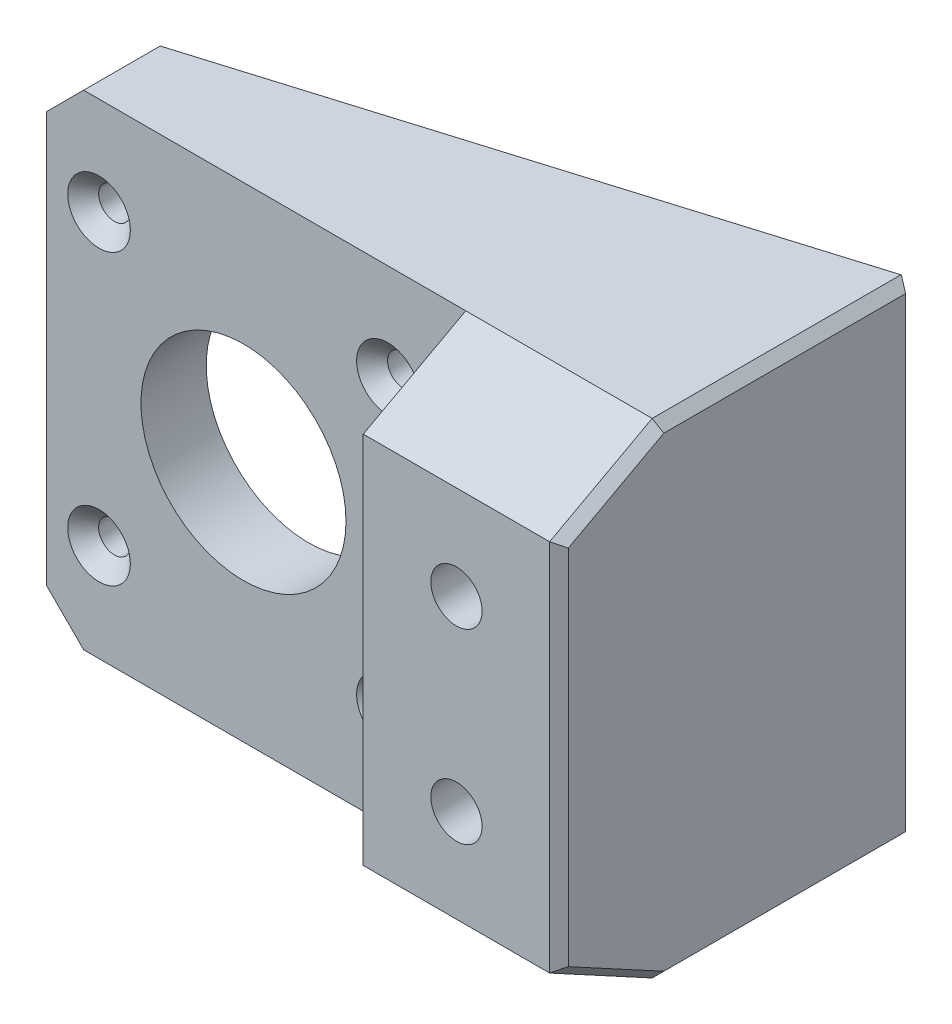
SolidWorks part; units mm, degrees
ref_plane "Front Plane" through (0, 0, 0) normal (0, 0, 1) x (1, 0, 0)
ref_plane "Top Plane" through (0, 0, 0) normal (0, 1, 0) x (1, 0, 0)
ref_plane "Right Plane" through (0, 0, 0) normal (1, 0, 0) x (0, 0, -1)
sketch "Sketch3" plane through (0, 0, 0) normal (0, 1, 0) x (1, 0, 0)
  line L0 (-22.5, -7) -> (22.5, -7)
  line L1 (22.5, -7) -> (22.5, -18)
  line L2 (22.5, -18) -> (43.5, -18)
  line L3 (43.5, -18) -> (43.5, 0)
  line L4 (43.5, 0) -> (-22.5, 0)
  line L5 (-22.5, 0) -> (-22.5, -7)
  point P4 (0, -7)
  dimension "D1" = 45
  dimension "D2" = 7
  dimension "D3" = 18
  dimension "D4" = 21
extrude "Boss-Extrude2" add sketch "Sketch3" along normal mid plane 52
sketch "Sketch5" plane through (0, 0, 7) normal (0, 0, 1) x (1, 0, 0)
  circle A0 centre (-1.35, 0) radius 11 construction
  circle A1 centre (-1.35, 0) radius 11
extrude "Cut-Extrude1" cut sketch "Sketch5" against normal through all
sketch "Sketch6" plane through (0, 0, 7) normal (0, 0, 1) x (1, 0, 0)
  point P0 (-16.85, -15.5)
  point P1 (-16.85, 15.5)
  point P3 (14.15, 15.5)
  point P5 (14.15, -15.5)
hole_wizard "CSK for M3 SFHCS1" positions "Sketch6" profile "Sketch7" countersink size "M3" standard "ANSI Metric" end condition through all
sketch "Sketch7" plane through (-16.85, -15.5, 7) normal (1, 0, 0) x (0, -1, 0)
  line L0 (0, 0) -> (0, 7)
  line L1 (0, 7) -> (1.7, 7)
  line L2 (1.7, 7) -> (1.7, 1.66)
  line L3 (1.7, 1.66) -> (3.36, 0)
  line L5 (3.36, 0) -> (0, 0)
  line L6 (-1.7, 1.66) -> (-3.36, 0) construction
  line L11 (0, -6.35) -> (0, 107.95) construction
  dimension "Thru Hole Dia." = 3.4
  dimension "Thru Hole Depth" = 7
  dimension "Near C'Sink Dia." = 6.72
  dimension "Near C'Sink Angle" = 90
sketch "Sketch9" plane through (0, 26, 0) normal (0, 1, 0) x (1, 0, 0)
  line L0 (-22.5, 0) -> (43.5, 20)
  line L1 (43.5, 20) -> (43.5, 0)
  line L2 (-22.5, 0) -> (43.5, 0)
  dimension "D1" = 20
extrude "Boss-Extrude4" add sketch "Sketch9" against normal up to surface (52 mm away) up to face at (14.5, -26, 8.3333)
sketch "Sketch10" plane through (0, 0, 0) normal (0, 0, 1) x (1, 0, 0)
  line L16 (19.85, -17.0898) -> (19.85, 17.0898)
  line L17 (19.85, 17.0898) -> (15.7398, 21.2)
  line L18 (15.7398, 21.2) -> (-18.4398, 21.2)
  line L19 (-18.4398, 21.2) -> (-22.55, 17.0898)
  line L20 (-22.55, 17.0898) -> (-22.55, -17.0898)
  line L21 (-22.55, -17.0898) -> (-18.4398, -21.2)
  line L22 (-18.4398, -21.2) -> (15.7398, -21.2)
  line L23 (15.7398, -21.2) -> (19.85, -17.0898)
  line L24 (19.85, -17.0898) -> (19.85, 17.0898)
  line L25 (19.85, 17.0898) -> (15.7398, 21.2)
  line L26 (15.7398, 21.2) -> (-18.4398, 21.2)
  line L27 (-18.4398, 21.2) -> (-22.55, 17.0898)
  line L28 (-22.55, 17.0898) -> (-22.55, -17.0898)
  line L29 (-22.55, -17.0898) -> (-18.4398, -21.2)
  line L30 (-18.4398, -21.2) -> (15.7398, -21.2)
  line L31 (15.7398, -21.2) -> (19.85, -17.0898)
  dimension "D1" = 0.2
extrude "Cut-Extrude2" cut sketch "Sketch10" against normal through all
sketch "Sketch11" plane through (0, 0, 0) normal (0, 0, -1) x (-1, 0, 0)
  point P0 (-32.5, 9.9586)
  point P1 (-32.5, -10.0414)
hole_wizard "CBORE for M5 SHCS1" positions "Sketch11" profile "Sketch12" counterbore size "M5" standard "ANSI Metric"
sketch "Sketch12" plane through (32.5, 9.9586, 0) normal (1, 0, 0) x (0, 1, 0)
  line L0 (0, 0) -> (0, 18)
  line L1 (0, 18) -> (2.75, 18)
  line L3 (2.75, 18) -> (2.75, 5)
  line L4 (2.75, 5) -> (5, 5)
  line L5 (5, 5) -> (5, 0)
  line L7 (5, 0) -> (0, 0)
  line L11 (0, -6.35) -> (0, 107.95) construction
  dimension "Thru Hole Dia." = 5.5
  dimension "Thru Hole Depth" = 18
  dimension "C'Bore Dia." = 10
  dimension "C'Bore Depth" = 5
sketch "Sketch13" plane through (0, 0, 0) normal (0, 0, 1) x (1, 0, 0)
  circle A0 centre (32.5, -10.0414) radius 5 construction
  circle A1 centre (32.5, 9.9586) radius 5 construction
  circle A2 centre (32.5, -10.0414) radius 5
  circle A3 centre (32.5, 9.9586) radius 5
extrude "Cut-Extrude3" cut sketch "Sketch13" against normal through all
sketch "Sketch14" plane through (22.5, 0, 0) normal (-1, 0, 0) x (0, 0, 1)
  line L0 (7, -26) -> (18, -20.0414)
  line L1 (18, 26) -> (18, -26) construction
  line L2 (18, -20.0414) -> (18, -26)
  line L3 (18, -26) -> (7, -26)
  point P5 (18, -20.0414)
extrude "Cut-Extrude4" cut sketch "Sketch14" against normal through all
mirror "Mirror2" about plane through (0, 0, 0) normal (0, 1, 0) of "Cut-Extrude4"
chamfer "Chamfer1" distance 1 angle 45 6 edges at (43.5, 0, -20) (43.5, 26, -6.5) (43.5, -26, -6.5) (43.5, -23.0207, 12.5) (43.5, 0, 18) (43.5, 23.0207, 12.5)
chamfer "Chamfer2" distance 4 angle 45 2 edges at (-22.5, 26, 3.5) (-22.5, -26, 3.5)
